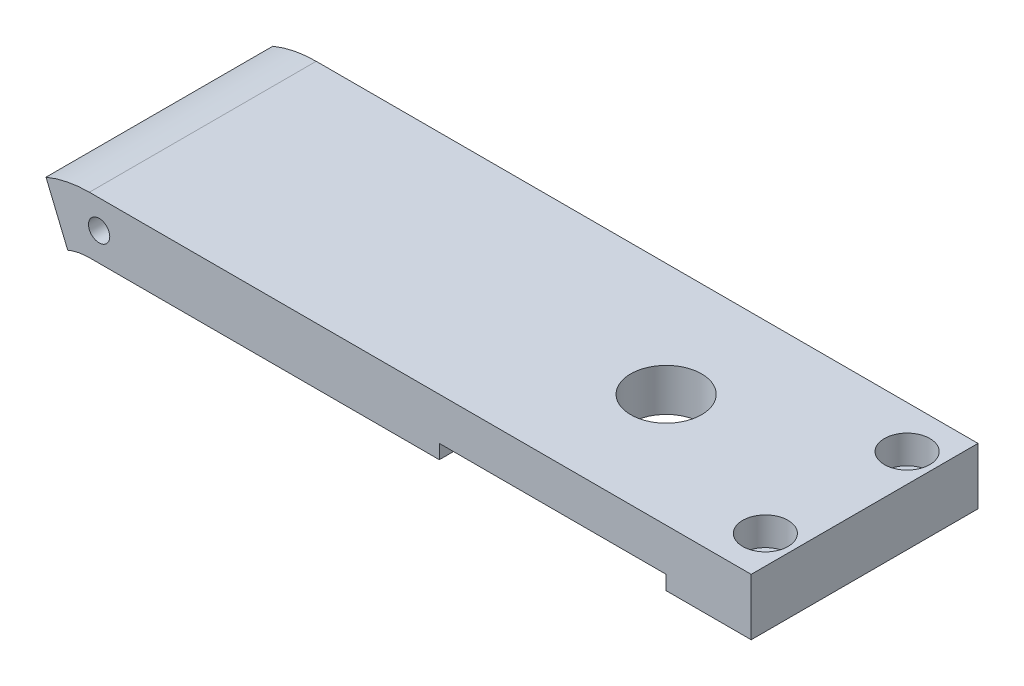
SolidWorks part; units mm, degrees
material "6061 Alloy"
ref_plane "Front Plane" through (0, 0, 0) normal (0, 0, 1) x (1, 0, 0)
ref_plane "Top Plane" through (0, 0, 0) normal (0, 1, 0) x (1, 0, 0)
ref_plane "Right Plane" through (0, 0, 0) normal (1, 0, 0) x (0, 0, -1)
sketch "Sketch1" plane through (0, 0, 0) normal (0, 0, 1) x (1, 0, 0)
  line L0 (0, 0) -> (-5.2605, 12.7)
  line L1 (-5.2605, 12.7) -> (153.4895, 12.7)
  line L2 (153.4895, 12.7) -> (153.4895, 0)
  line L3 (153.4895, 0) -> (0, 0)
  dimension "D1" = 158.75
  dimension "D2" = 112.5
  dimension "D3" = 12.7
extrude "Extrude1" add sketch "Sketch1" along normal blind 50.8
sketch "Sketch2" plane through (0, 0, 0) normal (0, -1, 0) x (1, 0, 0)
  line L0 (0, 50.8) -> (0, 0) construction
  line L1 (19.05, 41.275) -> (63.5, 41.275)
  line L2 (12.7, 34.925) -> (12.7, 15.875)
  line L3 (19.05, 9.525) -> (63.5, 9.525)
  line L4 (69.85, 34.925) -> (69.85, 15.875)
  line L5 (0, 50.8) -> (153.4895, 50.8) construction
  arc A0 (19.05, 41.275) -> (12.7, 34.925) centre (19.05, 34.925) ccw
  arc A1 (63.5, 41.275) -> (69.85, 34.925) centre (63.5, 34.925) cw
  arc A2 (63.5, 9.525) -> (69.85, 15.875) centre (63.5, 15.875) ccw
  arc A3 (12.7, 15.875) -> (19.05, 9.525) centre (19.05, 15.875) ccw
  dimension "D1" = 6.35
  dimension "D2" = 12.7
  dimension "D3" = 57.15
  dimension "D4" = 31.75
  dimension "D5" = 9.525
extrude "Cut-Extrude1" cut sketch "Sketch2" against normal blind 9.525
sketch "Sketch3" plane through (0, 0, 0) normal (0, -1, 0) x (1, 0, 0)
  line L0 (153.4895, 50.8) -> (153.4895, 0) construction
  line L1 (0, 50.8) -> (153.4895, 50.8) construction
  circle A0 centre (109.0395, 25.4) radius 7.9375
  dimension "D3" = 15.875
  dimension "D1" = 44.45
  dimension "D2" = 25.4
extrude "Cut-Extrude2" cut sketch "Sketch3" against normal through all
sketch "Sketch4" plane through (0, 0, 0) normal (0, -1, 0) x (1, 0, 0)
  line L0 (0, 50.8) -> (153.4895, 50.8) construction
  line L1 (83.6395, 50.8) -> (134.4395, 50.8)
  line L2 (83.6395, 50.8) -> (83.6395, 0)
  line L3 (83.6395, 0) -> (134.4395, 0)
  line L4 (134.4395, 50.8) -> (134.4395, 0)
  line L5 (0, 0) -> (153.4895, 0) construction
  circle A0 centre (109.0395, 25.4) radius 7.9375 construction
  dimension "D2" = 25.4
  dimension "D1" = 50.8
extrude "Cut-Extrude3" cut sketch "Sketch4" against normal blind 3.175
sketch "Sketch5" plane through (0, 0, 50.8) normal (0, 0, 1) x (1, 0, 0)
  line L0 (153.4895, 12.7) -> (-5.2605, 12.7) construction
  line L1 (153.4895, 0) -> (153.4895, 12.7) construction
  circle A0 centre (7.4395, 6.35) radius 2.3813
  dimension "D1" = 4.7625
  dimension "D2" = 6.35
  dimension "D3" = 146.05
extrude "Cut-Extrude4" cut sketch "Sketch5" against normal blind 15.875
sketch "Sketch6" plane through (0, 0, 0) normal (0, 0, -1) x (-1, 0, 0)
  circle A0 centre (-7.4395, 6.35) radius 2.3813
  circle A1 centre (-7.4395, 6.35) radius 2.3812 construction
  dimension "D1" = 4.7625
extrude "Cut-Extrude5" cut sketch "Sketch6" against normal blind 15.875
sketch "Sketch7" plane through (0, 12.7, 0) normal (0, 1, 0) x (-1, 0, 0)
  line L0 (-153.4895, 50.8) -> (-153.4895, 0) construction
  line L1 (-153.4895, 0) -> (5.2605, 0) construction
  line L2 (-153.4895, 50.8) -> (5.2605, 50.8) construction
  circle A0 centre (-147.1395, 9.525) radius 3.175
  circle A1 centre (-147.1395, 41.275) radius 3.175
  dimension "D1" = 6.35
  dimension "D2" = 6.35
  dimension "D3" = 6.35
  dimension "D4" = 6.35
  dimension "D5" = 9.525
  dimension "D6" = 9.525
extrude "Cut-Extrude6" cut sketch "Sketch7" against normal through all
sketch "Sketch8" plane through (0, 12.7, 0) normal (0, 1, 0) x (-1, 0, 0)
  circle A0 centre (-147.1395, 9.525) radius 5.08
  circle A1 centre (-147.1395, 41.275) radius 5.08
  dimension "D1" = 10.16
  dimension "D2" = 10.16
extrude "Cut-Extrude7" cut sketch "Sketch8" against normal blind 6.35
sketch "Sketch9" plane through (0, 0, 50.8) normal (0, 0, 1) x (1, 0, 0)
  line L0 (153.4895, 12.7) -> (-5.2605, 12.7) construction
  line L2 (-5.2605, 12.7) -> (0, 0) construction
  line L4 (5.2605, 12.7) -> (-5.2605, 12.7)
  line L5 (-5.2605, 12.7) -> (-4.4596, 10.7665)
  arc A0 (5.2605, 12.7) -> (-4.4596, 10.7665) centre (5.2605, -12.7) ccw
  dimension "D1" = 25.4
extrude "Cut-Extrude8" cut sketch "Sketch9" against normal through all
sketch "Sketch10" plane through (0, 0, 50.8) normal (0, 0, 1) x (1, 0, 0)
  line L0 (0, 0) -> (83.6395, 0) construction
  line L1 (0, 0) -> (0.4004, -0.9667)
  line L2 (0, 0) -> (5.2605, 0)
  line L3 (-4.4596, 10.7665) -> (0, 0) construction
  arc A0 (5.2605, 0) -> (0.4004, -0.9667) centre (5.2605, -12.7) ccw
  arc A1 (5.2605, 12.7) -> (-4.4596, 10.7665) centre (5.2605, -12.7) ccw construction
extrude "Extrude2" add sketch "Sketch10" against normal up to surface (50.8 mm away) up to face at (5.0582, 6.35, 0)
